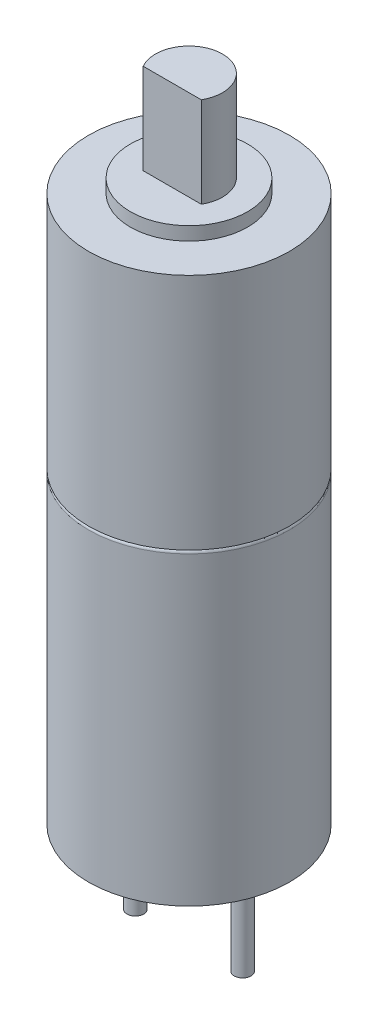
SolidWorks part; units mm, degrees
ref_plane "Front Plane" through (0, 0, 0) normal (0, 0, 1) x (1, 0, 0)
ref_plane "Top Plane" through (0, 0, 0) normal (0, 1, 0) x (1, 0, 0)
ref_plane "Right Plane" through (0, 0, 0) normal (1, 0, 0) x (0, 0, -1)
sketch "Sketch1" plane through (0, 0, 0) normal (0, 1, 0) x (1, 0, 0)
  circle A0 centre (0, 0) radius 3
  dimension "D1" = 6
extrude "Boss-Extrude1" add sketch "Sketch1" along normal blind 9.2
fillet "Fillet1" radius 0.1 1 edges at (0, 9.2, 3)
sketch "Sketch4" plane through (0, 9.2, 0) normal (0, 1, 0) x (1, 0, 0)
  circle A0 centre (0, 0) radius 3
  dimension "D1" = 6
extrude "Boss-Extrude4" add sketch "Sketch4" along normal blind 7.1
sketch "Sketch6" plane through (0, 16.3, 0) normal (0, 1, 0) x (1, 0, 0)
  circle A0 centre (0, 0) radius 1.75
  dimension "D1" = 3.5
extrude "Boss-Extrude6" add sketch "Sketch6" along normal blind 0.4
sketch "Sketch5" plane through (0, 16.3, 0) normal (0, 1, 0) x (1, 0, 0)
  line L0 (0, 1) -> (0, -0.5) construction
  line L1 (-0.866, -0.5) -> (0, -0.5)
  line L2 (0, -0.5) -> (0.866, -0.5)
  arc A0 (0.866, -0.5) -> (-0.866, -0.5) centre (0, 0) ccw
  dimension "D1" = 2
  dimension "D2" = 1.5
extrude "Boss-Extrude5" add sketch "Sketch5" along normal blind 3.1
sketch "Sketch7" plane through (0, 0, 0) normal (0, -1, 0) x (1, 0, 0)
  line L0 (0, 0) -> (0, 3) construction
  line L1 (0, 0) -> (-3, 0) construction
  circle A0 centre (0, 0) radius 3 construction
  circle A1 centre (-1.6, 0) radius 0.25
  circle A2 centre (1.6, 0) radius 0.25
  dimension "D1" = 0.5
  dimension "D2" = 3.2
extrude "Boss-Extrude7" add sketch "Sketch7" along normal blind 3
sketch "Sketch8" plane through (0, 0, 0) normal (0, -1, 0) x (1, 0, 0)
  line L0 (0, 0) -> (0, 3) construction
  circle A0 centre (0, 0) radius 3 construction
equation "\"supportThickness\"=3.2"
